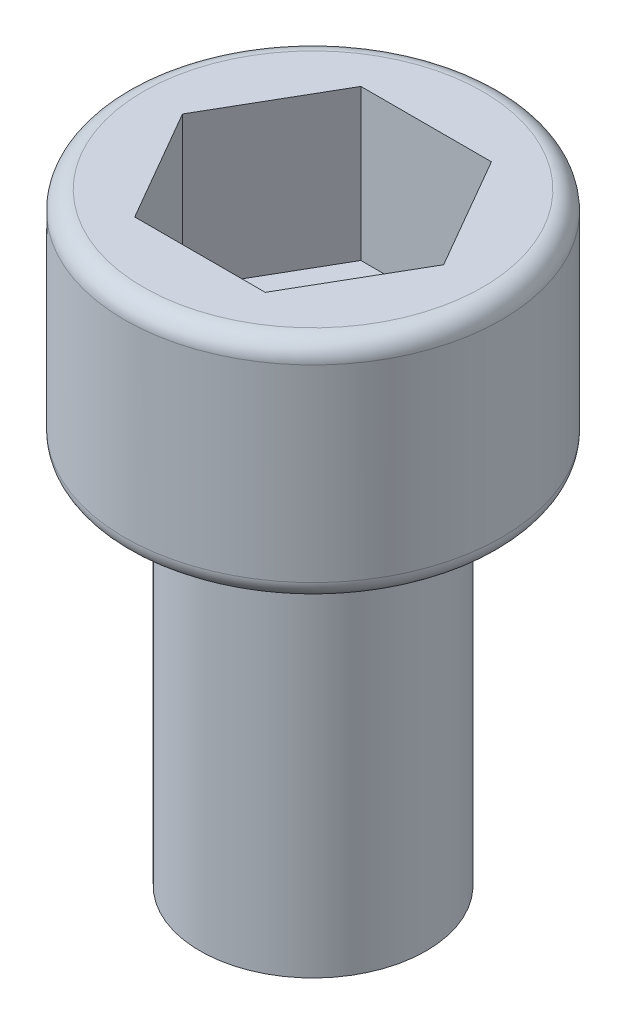
SolidWorks part; units mm, degrees
material "Galvanized Steel"
ref_plane "Front Plane" through (0, 0, 0) normal (0, 0, 1) x (1, 0, 0)
ref_plane "Top Plane" through (0, 0, 0) normal (0, 1, 0) x (1, 0, 0)
ref_plane "Right Plane" through (0, 0, 0) normal (1, 0, 0) x (0, 0, -1)
sketch "Sketch1" plane through (0, 0, 0) normal (0, 0, 1) x (1, 0, 0)
  line L0 (0, -4) -> (1.5, -4)
  line L1 (1.5, -4) -> (1.5, 1)
  line L2 (1.5, 1) -> (2.5, 1)
  line L3 (2.5, 1) -> (2.5, 4)
  line L4 (2.5, 4) -> (0, 4)
  line L5 (0, 4) -> (0, -4)
  line L6 (0, -1000) -> (0, 49000) construction
  point P2 (0, 0)
  dimension "D1" = 3
  dimension "D2" = 5
  dimension "D3" = 3
  dimension "D4" = 5
revolve "Revolve1" add sketch "Sketch1" angle 360 about L6
sketch "Sketch2" plane through (0, 4, 0) normal (0, 1, 0) x (1, 0, 0)
  line L1 (0.866, 1.5) -> (-0.866, 1.5)
  line L2 (-0.866, 1.5) -> (-1.7321, 0)
  line L3 (-1.7321, 0) -> (-0.866, -1.5)
  line L4 (-0.866, -1.5) -> (0.866, -1.5)
  line L5 (0.866, -1.5) -> (1.7321, 0)
  line L6 (1.7321, 0) -> (0.866, 1.5)
  circle A0 centre (0, 0) radius 1.5 construction
  dimension "D1" = 3
extrude "Cut-Extrude1" cut sketch "Sketch2" against normal blind 2
fillet "Fillet1" radius 0.25 2 edges at (2.5, 1, 0) (2.5, 4, 0)
